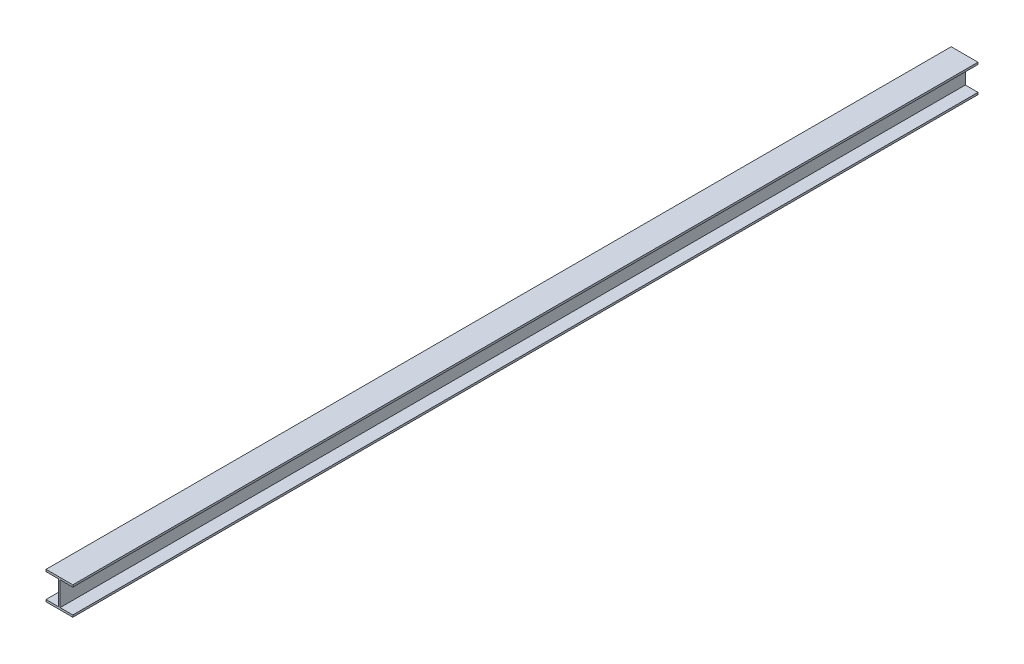
SolidWorks part; units mm, degrees
material "ASTM A992 Steel"
ref_plane "Front" through (0, 0, 0) normal (0, 0, 1) x (1, 0, 0)
ref_plane "Top" through (0, 0, 0) normal (0, 1, 0) x (1, 0, 0)
ref_plane "Right" through (0, 0, 0) normal (1, 0, 0) x (0, 0, -1)
sketch "Sketch1" plane through (0, 0, 0) normal (0, 0, 1) x (1, 0, 0)
  line L0 (0, -0.0002) -> (154.432, -0.0002)
  line L1 (154.432, -0.0002) -> (154.432, -11.5572)
  line L2 (154.432, -11.5572) -> (81.28, -11.5572)
  line L3 (81.28, -11.5572) -> (81.28, -150.4952)
  line L4 (81.28, -150.4952) -> (154.432, -150.4952)
  line L5 (154.432, -150.4952) -> (154.432, -162.0522)
  line L6 (154.432, -162.0522) -> (0, -162.0522)
  line L7 (0, -162.0522) -> (0, -150.4952)
  line L8 (0, -150.4952) -> (73.152, -150.4952)
  line L9 (73.152, -150.4952) -> (73.152, -11.5572)
  line L10 (73.152, -11.5572) -> (0, -11.5572)
  line L11 (0, -11.5572) -> (0, -0.0002)
  line L12 (77.216, -0.0002) -> (77.216, -162.0522) construction
  point P15 (154.432, -156.2737)
  dimension "D1" = 8.128
  dimension "D2" = 11.557
  dimension "D3" = 11.557
  dimension "D4" = 11.557
  dimension "D5" = 162.052
  dimension "D6" = 4.064
  dimension "D7" = 77.216
  dimension "D8" = 77.216
extrude "Boss-Extrude1" add sketch "Sketch1" along normal blind 5214.4
sketch "Sketch2" plane through (0, -162.0522, 0) normal (0, -1, 0) x (1, 0, 0)
  line L0 (0, 5214.4) -> (0, 0) construction
  line L1 (154.432, 5214.4) -> (154.432, 0) construction
  line L3 (154.432, 2607.2) -> (154.432, 2759.6)
  line L4 (154.432, 2759.6) -> (-279.5172, 2759.6)
  line L5 (-279.5172, 2607.2) -> (-279.5172, 2759.6)
  line L8 (154.432, 2607.2) -> (154.432, 2454.8)
  line L9 (154.432, 2454.8) -> (-279.5172, 2454.8)
  line L10 (-279.5172, 2607.2) -> (-279.5172, 2454.8)
  point P0 (0, 2607.2)
  dimension "D1" = 152.4
  dimension "D2" = 152.4
split line "Split Line1"
sketch "Sketch3" plane through (0, -162.0522, 0) normal (0, -1, 0) x (1, 0, 0)
  line L0 (0, 5214.4) -> (0, 2759.6) construction
  line L1 (0, 4616.38) -> (154.432, 4616.38)
  line L2 (0, 4616.38) -> (0, 4311.58)
  line L3 (0, 4311.58) -> (154.432, 4311.58)
  line L4 (154.432, 4616.38) -> (154.432, 4311.58)
  line L5 (154.432, 5214.4) -> (154.432, 2759.6) construction
  line L6 (81.28, 2607.2) -> (-198.991, 2607.2) construction
  line L7 (81.28, 5214.4) -> (81.28, 0) construction
  line L8 (154.432, 598.02) -> (154.432, 902.82)
  line L9 (0, 902.82) -> (154.432, 902.82)
  line L10 (0, 598.02) -> (0, 902.82)
  line L11 (0, 598.02) -> (154.432, 598.02)
  dimension "D1" = 304.8
split line "Split Line2"
